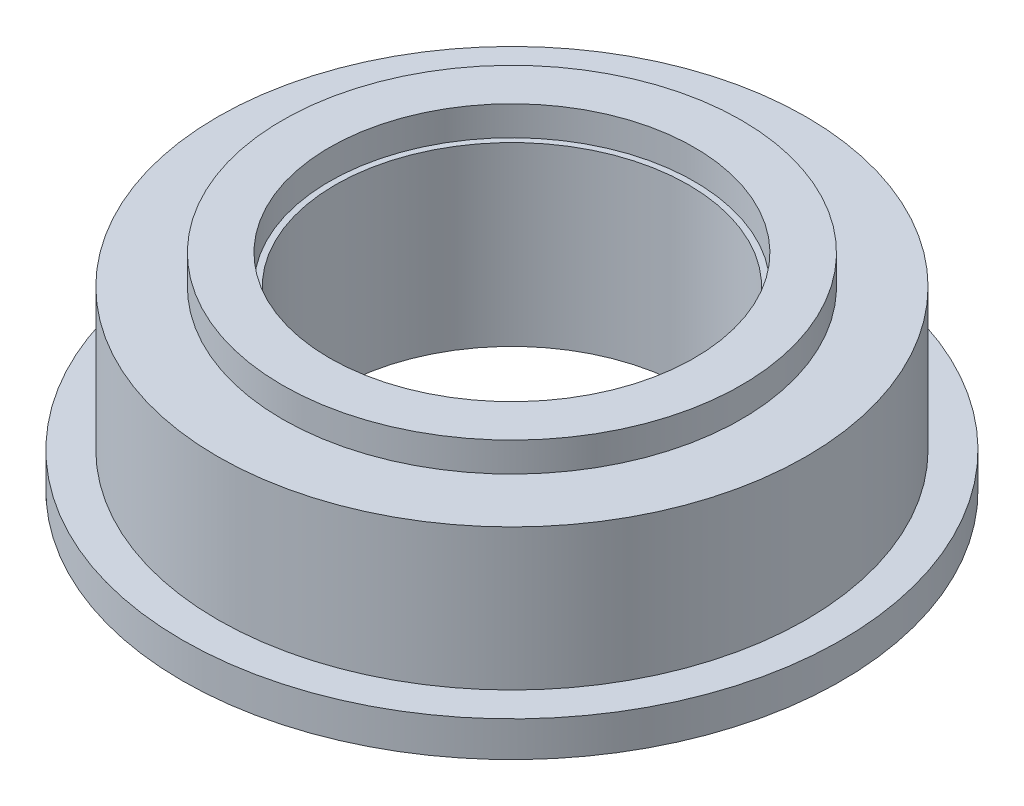
SolidWorks part; units mm, degrees
ref_plane "前视基准面" through (0, 0, 0) normal (0, 0, 1) x (1, 0, 0)
ref_plane "上视基准面" through (0, 0, 0) normal (0, 1, 0) x (1, 0, 0)
ref_plane "右视基准面" through (0, 0, 0) normal (1, 0, 0) x (0, 0, -1)
sketch "草图1" plane through (0, 0, 0) normal (0, 1, 0) x (1, 0, 0)
  circle A0 centre (0, 0) radius 3
  circle A1 centre (0, 0) radius 5.6
  dimension "D1" = 11.2
  dimension "D2" = 6
extrude "凸台-拉伸1" add sketch "草图1" along normal blind 0.6
sketch "草图2" plane through (0, 0.6, 0) normal (0, 1, 0) x (1, 0, 0)
  circle A0 centre (0, 0) radius 5
  circle A1 centre (0, 0) radius 3
  circle A2 centre (0, 0) radius 3 construction
  dimension "D1" = 10
extrude "凸台-拉伸2" add sketch "草图2" along normal blind 2.4
sketch "草图3" plane through (0, 3, 0) normal (0, 1, 0) x (1, 0, 0)
  circle A0 centre (0, 0) radius 3.1
  circle A1 centre (0, 0) radius 3.9
  circle A2 centre (0, 0) radius 3 construction
  dimension "D1" = 0.1
  dimension "D2" = 0.8
extrude "凸台-拉伸3" add sketch "草图3" along normal blind 0.5
